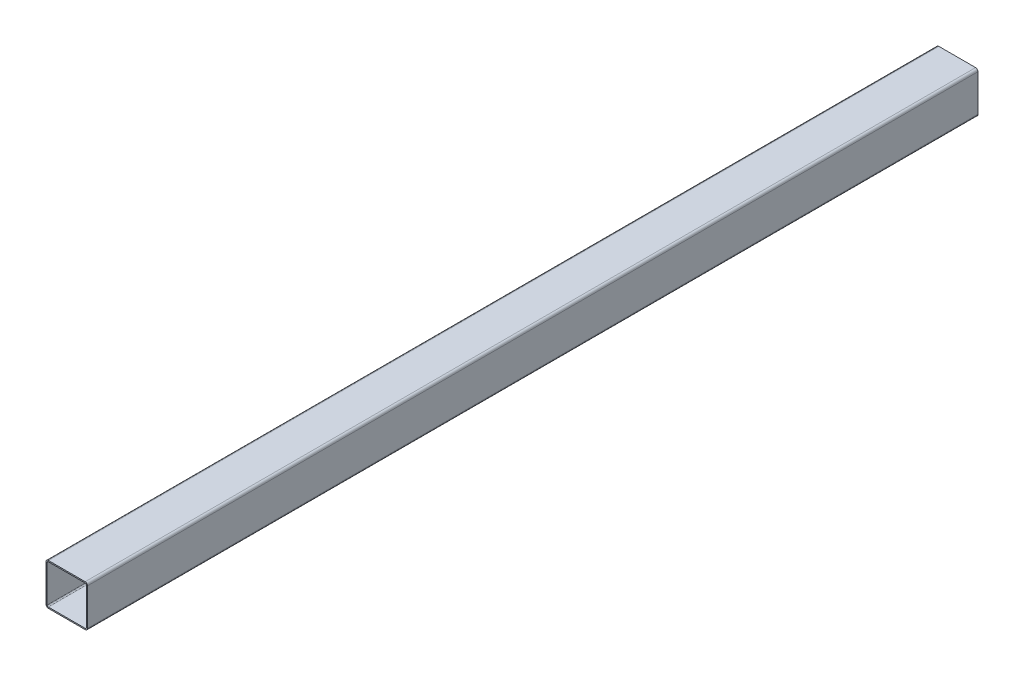
SolidWorks part; units mm, degrees
material "ASTM A36 Steel"
ref_plane "Front Plane" through (0, 0, 0) normal (0, 0, 1) x (1, 0, 0)
ref_plane "Top Plane" through (0, 0, 0) normal (0, 1, 0) x (1, 0, 0)
ref_plane "Right Plane" through (0, 0, 0) normal (1, 0, 0) x (0, 0, -1)
sketch "Sketch1" plane through (0, 0, 0) normal (0, 0, 1) x (1, 0, 0)
  line L1 (29.0579, 22.7025) -> (-32.9421, 22.7025)
  line L2 (33.0579, 18.7025) -> (33.0579, -43.2975)
  line L3 (29.0579, -47.2975) -> (-32.9421, -47.2975)
  line L4 (-36.9421, 18.7025) -> (-36.9421, -43.2975)
  line L5 (29.0579, 20.7025) -> (-32.9421, 20.7025)
  line L6 (31.0579, 18.7025) -> (31.0579, -43.2975)
  line L7 (29.0579, -45.2975) -> (-32.9421, -45.2975)
  line L8 (-34.9421, 18.7025) -> (-34.9421, -43.2975)
  arc A0 (29.0579, 22.7025) -> (33.0579, 18.7025) centre (29.0579, 18.7025) cw
  arc A1 (33.0579, -43.2975) -> (29.0579, -47.2975) centre (29.0579, -43.2975) cw
  arc A2 (-32.9421, -47.2975) -> (-36.9421, -43.2975) centre (-32.9421, -43.2975) cw
  arc A3 (-36.9421, 18.7025) -> (-32.9421, 22.7025) centre (-32.9421, 18.7025) cw
  arc A4 (29.0579, 20.7025) -> (31.0579, 18.7025) centre (29.0579, 18.7025) cw
  arc A5 (29.0579, -45.2975) -> (31.0579, -43.2975) centre (29.0579, -43.2975) ccw
  arc A6 (-32.9421, -45.2975) -> (-34.9421, -43.2975) centre (-32.9421, -43.2975) cw
  arc A7 (-34.9421, 18.7025) -> (-32.9421, 20.7025) centre (-32.9421, 18.7025) cw
  point P10 (33.0579, 22.7025)
  point P15 (-36.9421, -47.2975)
  point P18 (-36.9421, 22.7025)
  point P21 (31.0579, 20.7025)
  point P26 (-34.9421, -45.2975)
  point P29 (-34.9421, 20.7025)
  dimension "D7" = 4
  dimension "D8" = 2
  dimension "D1" = 70
  dimension "D2" = 70
  dimension "D3" = 66
  dimension "D4" = 66
  dimension "D5" = 2
  dimension "D6" = 2
extrude "Boss-Extrude1" add sketch "Sketch1" along normal blind 1500
